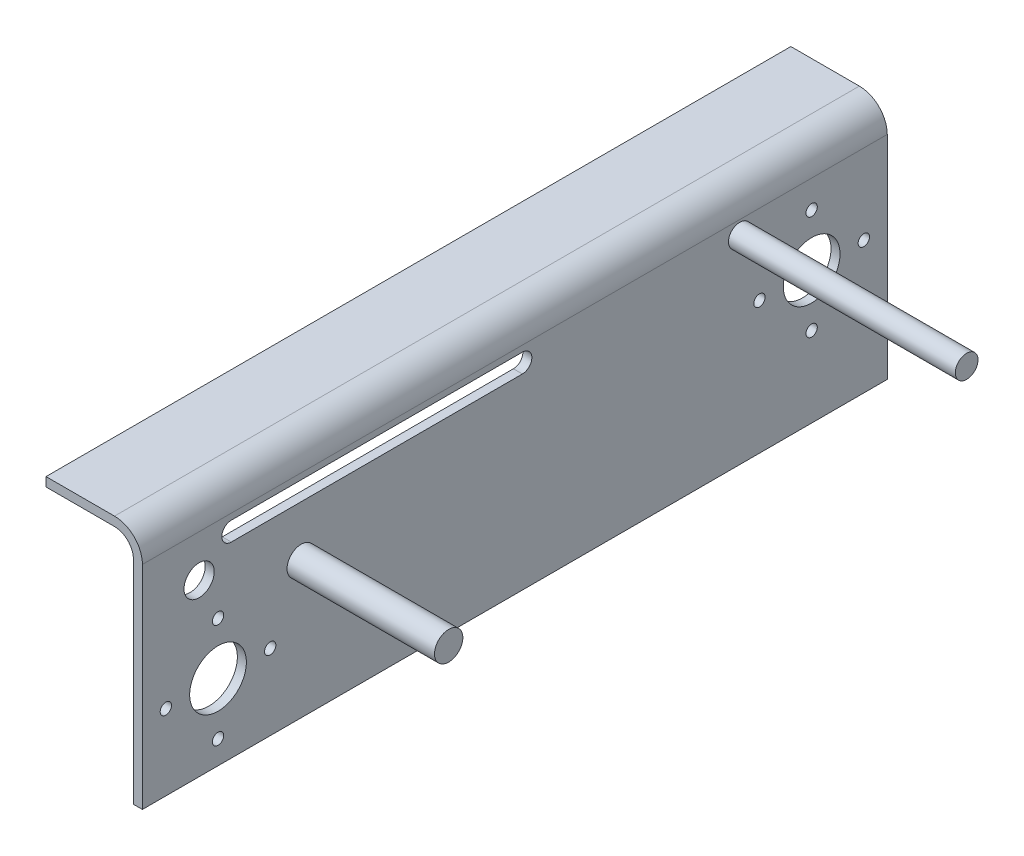
SolidWorks part; units mm, degrees
ref_plane "Alzado" through (0, 0, 0) normal (0, 0, 1) x (1, 0, 0)
ref_plane "Planta" through (0, 0, 0) normal (0, 1, 0) x (1, 0, 0)
ref_plane "Vista lateral" through (0, 0, 0) normal (1, 0, 0) x (0, 0, -1)
sketch "Croquis1" plane through (0, 0, 0) normal (0, 0, 1) x (1, 0, 0)
  line L0 (35.0356, 151.5715) -> (35.0356, 2.6893) construction
  line L1 (96.1647, 24.5715) -> (100.9272, 24.5715)
  line L2 (100.9272, 24.5715) -> (100.9272, 136.809)
  line L3 (96.1647, 24.5715) -> (96.1647, 136.809)
  line L4 (49.9272, 151.5715) -> (86.1647, 151.5715)
  line L5 (49.9272, 146.809) -> (49.9272, 151.5715)
  line L6 (49.9272, 146.809) -> (86.1647, 146.809)
  arc A0 (86.1647, 146.809) -> (96.1647, 136.809) centre (86.1647, 136.809) cw
  arc A1 (86.1647, 151.5715) -> (100.9272, 136.809) centre (86.1647, 136.809) cw
extrude "Saliente-Extruir1" add sketch "Croquis1" against normal blind 394
sketch "Croquis2" plane through (96.1647, 0, 0) normal (-1, 0, 0) x (0, 0, 1)
  line L5 (0, 175.9208) -> (0, 24.5715) construction
  line L6 (-394, 175.9208) -> (0, 175.9208) construction
  line L7 (-394, 24.5715) -> (-394, 175.9208) construction
  line L8 (0, 24.5715) -> (-394, 24.5715) construction
  circle A10 centre (-40, 36.9739) radius 3
  circle A11 centre (-12.4024, 64.5715) radius 3
  circle A12 centre (-67.5976, 64.5715) radius 3
  circle A13 centre (-40, 92.1691) radius 3
  circle A14 centre (-40, 64.5715) radius 15
  circle A15 centre (-326.4024, 94.5715) radius 3
  circle A16 centre (-354, 66.9739) radius 3
  circle A17 centre (-354, 94.5715) radius 15
  circle A18 centre (-381.5976, 94.5715) radius 3
  circle A19 centre (-354, 122.1691) radius 3
extrude "Cortar-Extruir1" cut sketch "Croquis2" against normal through all
sketch "Croquis4" plane through (100.9272, 0, 0) normal (1, 0, 0) x (0, 0, -1)
  line L0 (0, 24.5715) -> (0, 136.809) construction
  line L1 (394, 24.5715) -> (0, 24.5715) construction
  circle A0 centre (30, 114.5715) radius 8
  dimension "D1" = 16
  dimension "D2" = 30
  dimension "D3" = 90
extrude "Cortar-Extruir3" cut sketch "Croquis4" against normal through all
sketch "Croquis5" plane through (100.9272, 0, 0) normal (1, 0, 0) x (0, 0, -1)
  circle A0 centre (84, 96.5715) radius 7.5
  circle A1 centre (40, 64.5715) radius 15 construction
  dimension "D1" = 15
  dimension "D2" = 44
  dimension "D3" = 32
extrude "Saliente-Extruir2" add sketch "Croquis5" along normal blind 78
sketch "Croquis6" plane through (100.9272, 0, 0) normal (1, 0, 0) x (0, 0, -1)
  circle A0 centre (316, 129.5715) radius 6
  circle A1 centre (354, 94.5715) radius 15 construction
  dimension "D1" = 38
  dimension "D2" = 12
  dimension "D3" = 35
extrude "Saliente-Extruir3" add sketch "Croquis6" along normal blind 120
sketch "Croquis7" plane through (100.9272, 0, 0) normal (1, 0, 0) x (0, 0, -1)
  line L0 (47, 128.5715) -> (201, 128.5715) construction
  line L1 (47, 133.5715) -> (201, 133.5715)
  line L2 (47, 123.5715) -> (201, 123.5715)
  arc A0 (47, 133.5715) -> (47, 123.5715) centre (47, 128.5715) ccw
  arc A1 (201, 123.5715) -> (201, 133.5715) centre (201, 128.5715) ccw
  circle A2 centre (40, 64.5715) radius 15 construction
  point P2 (124, 128.5715)
  dimension "D3" = 84
  dimension "D1" = 154
  dimension "D2" = 10
  dimension "D4" = 64
extrude "Cortar-Extruir4" cut sketch "Croquis7" against normal through all
